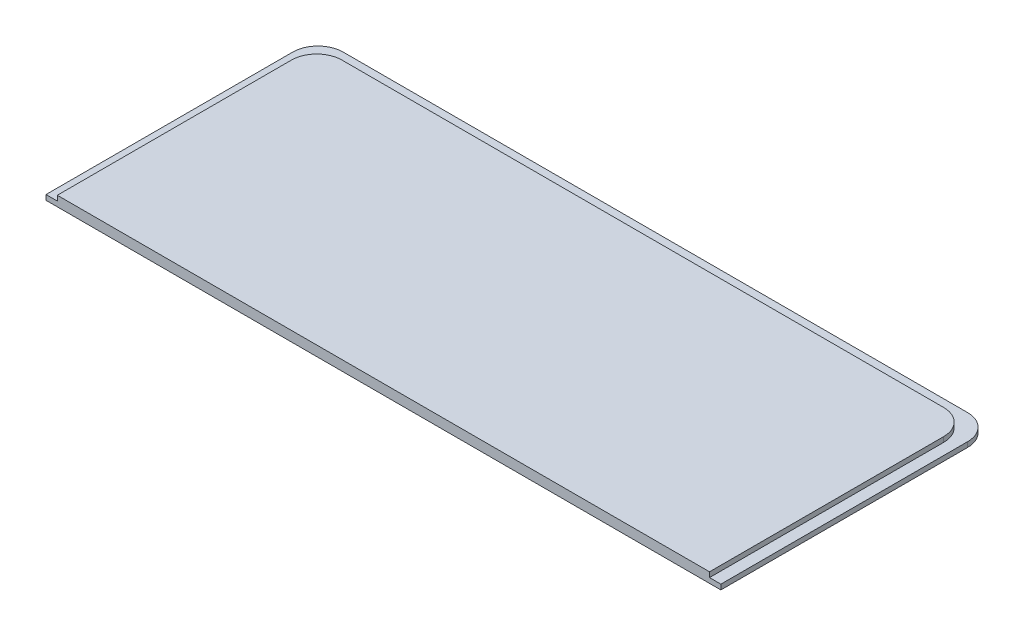
SolidWorks part; units mm, degrees
ref_plane "Front Plane" through (0, 0, 0) normal (0, 0, 1) x (1, 0, 0)
ref_plane "Top Plane" through (0, 0, 0) normal (0, 1, 0) x (1, 0, 0)
ref_plane "Right Plane" through (0, 0, 0) normal (1, 0, 0) x (0, 0, -1)
sketch "Sketch1" plane through (0, 0, 0) normal (0, 1, 0) x (1, 0, 0)
  line L1 (-59.75, 25.75) -> (59.75, 25.75)
  line L2 (-64.75, 20.75) -> (-64.75, -25.75)
  line L3 (-64.75, -25.75) -> (64.75, -25.75)
  line L4 (64.75, 20.75) -> (64.75, -25.75)
  line L5 (-64.75, 25.75) -> (64.75, -25.75) construction
  line L6 (-64.75, -25.75) -> (64.75, 25.75) construction
  arc A0 (-59.75, 25.75) -> (-64.75, 20.75) centre (-59.75, 20.75) ccw
  arc A1 (59.75, 25.75) -> (64.75, 20.75) centre (59.75, 20.75) cw
  point P0 (0, 0)
  dimension "D3" = 5
  dimension "D1" = 129.5
  dimension "D2" = 51.5
extrude "Boss-Extrude1" add sketch "Sketch1" along normal blind 2
sketch "Sketch2" plane through (0, 0, 0) normal (0, 1, 0) x (1, 0, 0)
  line L0 (-64.75, -25.75) -> (64.75, -25.75) construction
  line L1 (-67, -25.75) -> (67, -25.75)
  line L2 (-67, -25.75) -> (-67, 23.25)
  line L3 (-62, 28.25) -> (62, 28.25)
  line L4 (67, -25.75) -> (67, 23.25)
  arc A0 (62, 28.25) -> (67, 23.25) centre (62, 23.25) cw
  arc A1 (-67, 23.25) -> (-62, 28.25) centre (-62, 23.25) cw
  point P6 (0, -25.75)
  point P12 (-67, 28.25)
  dimension "D3" = 5
  dimension "D1" = 134
  dimension "D2" = 54
extrude "Boss-Extrude2" add sketch "Sketch2" along normal blind 1
